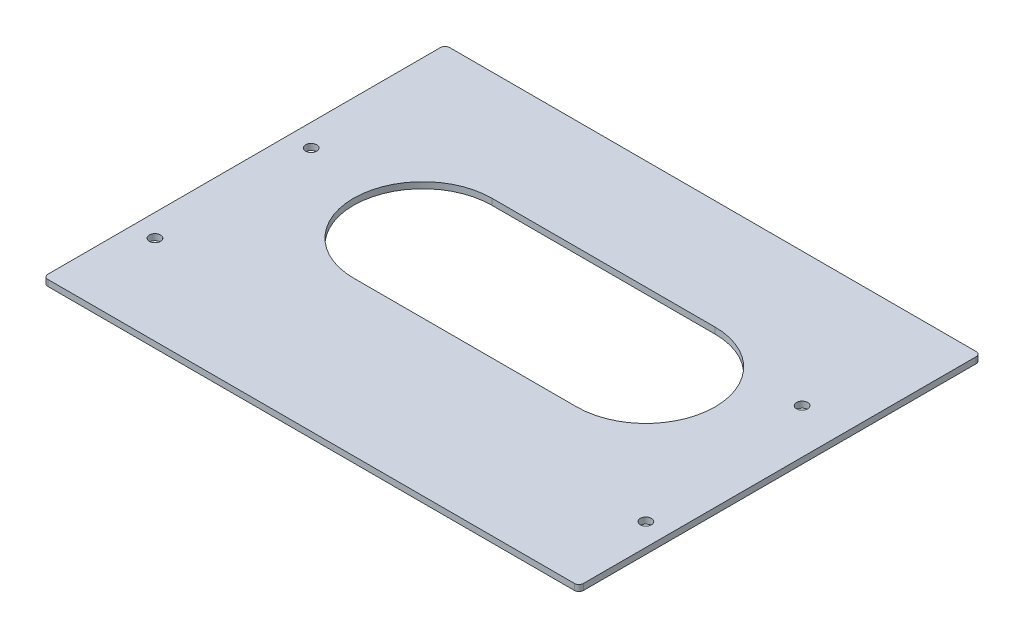
SolidWorks part; units mm, degrees
ref_plane "Front Plane" through (0, 0, 0) normal (0, 0, 1) x (1, 0, 0)
ref_plane "Top Plane" through (0, 0, 0) normal (0, 1, 0) x (1, 0, 0)
ref_plane "Right Plane" through (0, 0, 0) normal (1, 0, 0) x (0, 0, -1)
sketch "Sketch1" plane through (0, 0, 0) normal (0, 1, 0) x (1, 0, 0)
  line L1 (-126.9534, -0.978) -> (172.7666, -0.978)
  line L2 (-129.4934, -3.518) -> (-129.4934, -227.038)
  line L3 (-126.9534, -229.578) -> (172.7666, -229.578)
  line L4 (175.3066, -3.518) -> (175.3066, -227.038)
  arc A8 (172.7666, -0.978) -> (175.3066, -3.518) centre (172.7666, -3.518) cw
  arc A9 (175.3066, -227.038) -> (172.7666, -229.578) centre (172.7666, -227.038) cw
  arc A10 (-126.9534, -229.578) -> (-129.4934, -227.038) centre (-126.9534, -227.038) cw
  arc A11 (-129.4934, -3.518) -> (-126.9534, -0.978) centre (-126.9534, -3.518) cw
  dimension "D7" = 2.54
  dimension "D17" = 304.8
  dimension "D15" = 228.6
extrude "Boss-Extrude1" add sketch "Sketch1" along normal blind 3.5
sketch "Sketch7" plane through (0, 0, 0) normal (0, -1, 0) x (-1, 0, 0)
  line L0 (126.9534, -229.578) -> (-172.7666, -229.578) construction
  line L1 (40.5934, -141.948) -> (-86.4066, -141.948)
  line L2 (129.4934, -3.518) -> (129.4934, -227.038) construction
  line L3 (40.5934, -63.208) -> (-86.4066, -63.208)
  arc A2 (-86.4066, -63.208) -> (-86.4066, -141.948) centre (-86.4066, -102.578) ccw
  arc A3 (40.5934, -141.948) -> (40.5934, -63.208) centre (40.5934, -102.578) ccw
  point P0 (-22.9066, -102.578)
  dimension "D4" = 63.5
  dimension "D1" = 127
  dimension "D3" = 152.4
  dimension "D5" = 63.5
extrude "Cut-Extrude7" cut sketch "Sketch7" against normal through all contours L1 A2 L3 A3
sketch "Sketch8" plane through (0, 0, 0) normal (0, -1, 0) x (-1, 0, 0)
  line L0 (-172.7666, -0.978) -> (126.9534, -0.978) construction
  line L1 (-175.3066, -227.038) -> (-175.3066, -3.518) construction
  circle A0 centre (-149.9066, -77.178) radius 3.175
  circle A1 centre (116.7934, -89.878) radius 3.175
  circle A2 centre (116.7934, -178.778) radius 3.175
  circle A3 centre (-162.6066, -178.778) radius 3.175
  dimension "D1" = 76.2
  dimension "D3" = 25.4
extrude "Cut-Extrude8" cut sketch "Sketch8" against normal through all
